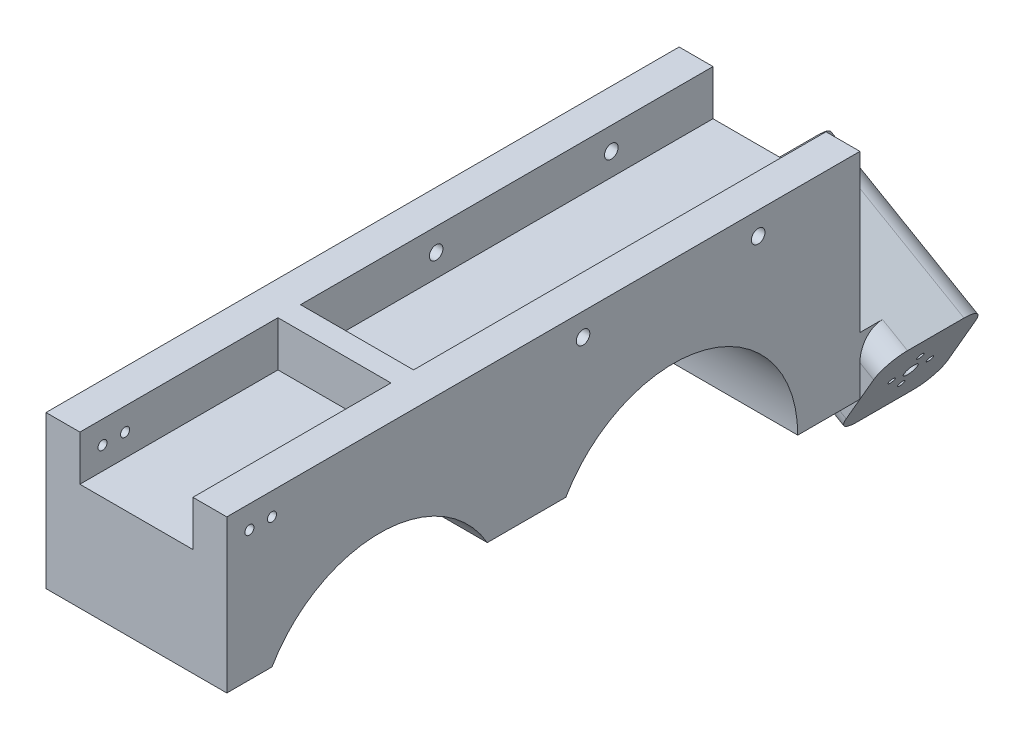
SolidWorks part; units mm, degrees
ref_plane "Спереди" through (0, 0, 0) normal (0, 0, 1) x (1, 0, 0)
ref_plane "Сверху" through (0, 0, 0) normal (0, 1, 0) x (1, 0, 0)
ref_plane "Справа" through (0, 0, 0) normal (1, 0, 0) x (0, 0, -1)
sketch "Эскиз1" plane through (0, 0, 0) normal (1, 0, 0) x (0, 0, -1)
  line L5 (0, 0) -> (0, -95)
  line L23 (-82.5, -95) -> (-130.1314, -67.5) construction
  line L24 (-27.5, -95) -> (0, -95)
  line L25 (-82.5, -95) -> (-27.5, -95) construction
  line L26 (-82.5, -95) -> (-82.5, -40) construction
  line L27 (-92.5, -40.9167) -> (-92.5, -50)
  line L28 (-92.5, -50) -> (-72.5, -50)
  line L29 (-72.5, -50) -> (-72.5, -40.9167)
  line L31 (-137.5, -95) -> (-157.5, -95) construction
  line L32 (-130.1314, -67.5) -> (-164.8686, -67.5)
  line L33 (-260.1314, -67.5) -> (-280.1314, -67.5)
  line L34 (0, 0) -> (-280.1314, 0)
  line L35 (-280.1314, 0) -> (-280.1314, -67.5)
  line L36 (-212.5, -95) -> (-212.5, 0) construction
  line L37 (-222.5, -40.9167) -> (-222.5, -50)
  line L38 (-222.5, -50) -> (-202.5, -50)
  line L39 (-202.5, -50) -> (-202.5, -40.9167)
  arc A6 (-130.1314, -67.5) -> (-92.5, -40.9167) centre (-82.5, -95) cw
  arc A7 (-72.5, -40.9167) -> (-27.5, -95) centre (-82.5, -95) cw
  arc A8 (-130.1314, -67.5) -> (-27.5, -95) centre (-82.5, -95) cw construction
  circle A12 centre (-45, -10) radius 3
  arc A13 (-27.5, -95) -> (-137.5, -95) centre (-82.5, -95) ccw construction
  arc A14 (-157.5, -95) -> (-202.5, -40.9167) centre (-212.5, -95) ccw construction
  arc A15 (-164.8686, -67.5) -> (-202.5, -40.9167) centre (-212.5, -95) ccw
  arc A16 (-222.5, -40.9167) -> (-267.5, -95) centre (-212.5, -95) ccw construction
  arc A17 (-222.5, -40.9167) -> (-260.1314, -67.5) centre (-212.5, -95) ccw
  arc A18 (-157.5, -95) -> (-267.5, -95) centre (-212.5, -95) ccw construction
  circle A19 centre (-122.5, -10) radius 3
  circle A20 centre (-270.1314, -10) radius 2
  circle A21 centre (-260.1314, -10) radius 2
  point P0 (0, 0)
  dimension "D1" = 27.5
  dimension "D4" = 10
  dimension "D3" = 20
  dimension "D2" = 55
  dimension "D8" = 40
  dimension "D12" = 10
  dimension "D14" = 6
  dimension "D13" = 20
  dimension "D6" = 20
  dimension "D10" = 10
  dimension "D17" = 4
  dimension "D5" = 60
  dimension "D7" = 20
  dimension "D9" = 37.5
  dimension "D11" = 40
  dimension "D15" = 10
  dimension "D16" = 10
extrude "Бобышка-Вытянуть1" add sketch "Эскиз1" along normal blind 80
sketch "Эскиз3" plane through (0, 0, 0) normal (0, 0, -1) x (-1, 0, 0)
  line L0 (-80, -95) -> (0, -48.812) construction
  line L3 (0, -95) -> (0, 0) construction
  line L4 (-80, -95) -> (0, -95) construction
  dimension "D1" = 30
ref_plane "Плоскость1" through (-21.1362, -36.609, 0) normal (0.5, 0.866, 0) x (-0.866, 0.5, 0)
sketch "Эскиз4" plane through (0, -50, 0) normal (0, -1, 0) x (1, 0, 0)
  line L5 (80, 72.5) -> (0, 72.5) construction
  line L6 (0, 92.5) -> (15, 92.5)
  line L11 (0, 92.5) -> (0, 72.5)
  line L12 (0, 72.5) -> (15, 72.5)
  line L18 (15, 92.5) -> (15, 72.5)
  line L20 (80, 92.5) -> (65, 92.5)
  line L21 (80, 92.5) -> (80, 72.5)
  line L22 (80, 72.5) -> (65, 72.5)
  line L23 (65, 92.5) -> (65, 72.5)
  dimension "D1" = 15
extrude "Вырез-Вытянуть4" cut sketch "Эскиз4" against normal up to surface (9.0833 mm away)
sketch "Эскиз5" plane through (-21.1362, -36.609, 0) normal (0.5, 0.866, 0) x (-0.866, 0.5, 0)
  line L1 (-116.782, 0) -> (-41.782, 0)
  line L2 (-116.782, 0) -> (-116.782, -45)
  line L3 (-116.782, -45) -> (-41.782, -45)
  line L4 (-41.782, 0) -> (-41.782, -45)
  dimension "D1" = 45
  dimension "D2" = 75
extrude "Бобышка-Вытянуть2" add sketch "Эскиз5" along normal mid plane 44.3
sketch "Эскиз10" plane through (36.1843, -20.891, 0) normal (-0.866, 0.5, 0) x (0, 0, 1)
  line L0 (-22.5, -64.4224) -> (-22.5, -20.1224) construction
  line L1 (-45, -64.4224) -> (0, -64.4224) construction
  line L2 (-45, -20.1224) -> (0, -20.1224) construction
  line L3 (-45, -42.2724) -> (-74.0238, -42.2724) construction
  line L4 (-45, -20.1224) -> (-45, -64.4224) construction
  line L5 (50.8068, -42.2724) -> (-50.8068, -42.2724) construction
  circle A0 centre (-22.5, -42.2724) radius 12.5
  dimension "D1" = 25
extrude "Вырез-Вытянуть5" cut sketch "Эскиз10" against normal blind 60 contours A0
sketch "Эскиз12" plane through (88.1458, -50.891, 0) normal (-0.866, 0.5, 0) x (0, 0, 1)
  line L0 (-45, -42.2724) -> (0, -42.2724) construction
  line L1 (-45, -20.1224) -> (-45, -64.4224) construction
  line L2 (0, -20.1224) -> (0, -64.4224) construction
  line L3 (-22.5, -20.1224) -> (-22.5, -64.4224) construction
  line L4 (-45, -20.1224) -> (0, -20.1224) construction
  line L5 (-45, -64.4224) -> (0, -64.4224) construction
  circle A0 centre (-22.5, -42.2724) radius 3
  circle A1 centre (-22.5, -33.7724) radius 1.5
  circle A2 centre (-14, -42.2724) radius 1.5
  circle A3 centre (-22.5, -50.7724) radius 1.5
  circle A4 centre (-31, -42.2724) radius 1.5
  point P25 (-22.5, -42.2724)
  dimension "D1" = 6
  dimension "D2" = 3
  dimension "D3" = 8.5
  dimension "D5" = 8.5
  dimension "D4" = 4
extrude "Вырез-Вытянуть6" cut sketch "Эскиз12" against normal up to surface (15 mm away) up to face at (80, -95, -18)
fillet "Скругление1" radius 10 4 edges at (85.5375, -72.6205, 0) (52.3125, -104.5912, 0) (36.449, -95.4325, -45) (58.599, -57.0675, -45)
sketch "Эскиз13" plane through (0, 0, 0) normal (0, 0, -1) x (-1, 0, 0)
  line L0 (-80, 0) -> (0, 0) construction
  line L1 (-65, 0) -> (-15, 0)
  line L2 (-65, 0) -> (-65, -20)
  line L3 (-65, -20) -> (-15, -20)
  line L4 (-15, 0) -> (-15, -20)
  dimension "D1" = 20
  dimension "D2" = 50
  dimension "D3" = 15
extrude "Вырез-Вытянуть7" cut sketch "Эскиз13" against normal up to surface (280.1314 mm away) up to face at (40, -33.75, 280.1314)
sketch "Эскиз14" plane through (0, -50, 0) normal (0, -1, 0) x (1, 0, 0)
  line L0 (80, 202.5) -> (0, 202.5) construction
  line L1 (0, 222.5) -> (15, 222.5)
  line L2 (0, 222.5) -> (0, 202.5)
  line L3 (0, 202.5) -> (15, 202.5)
  line L4 (15, 222.5) -> (15, 202.5)
  line L5 (80, 202.5) -> (0, 202.5) construction
  line L6 (80, 222.5) -> (65, 222.5)
  line L7 (80, 222.5) -> (80, 202.5)
  line L8 (80, 202.5) -> (65, 202.5)
  line L9 (65, 222.5) -> (65, 202.5)
  dimension "D1" = 15
extrude "Вырез-Вытянуть8" cut sketch "Эскиз14" against normal up to surface (9.0833 mm away)
sketch "Эскиз15" plane through (0, -20, 0) normal (0, 1, 0) x (1, 0, 0)
  line L0 (15, -280.1314) -> (15, 0) construction
  line L1 (15, -192.5) -> (65, -192.5)
  line L2 (15, -192.5) -> (15, -182.5)
  line L3 (15, -182.5) -> (65, -182.5)
  line L4 (65, -192.5) -> (65, -182.5)
  line L5 (65, -280.1314) -> (65, 0) construction
  line L6 (65, -92.5) -> (65, -72.5) construction
  point P10 (65, -82.5)
  dimension "D1" = 100
  dimension "D2" = 10
extrude "Бобышка-Вытянуть3" add sketch "Эскиз15" along normal up to surface (20 mm away) up to face at (7.5, 0, 140.0657)
